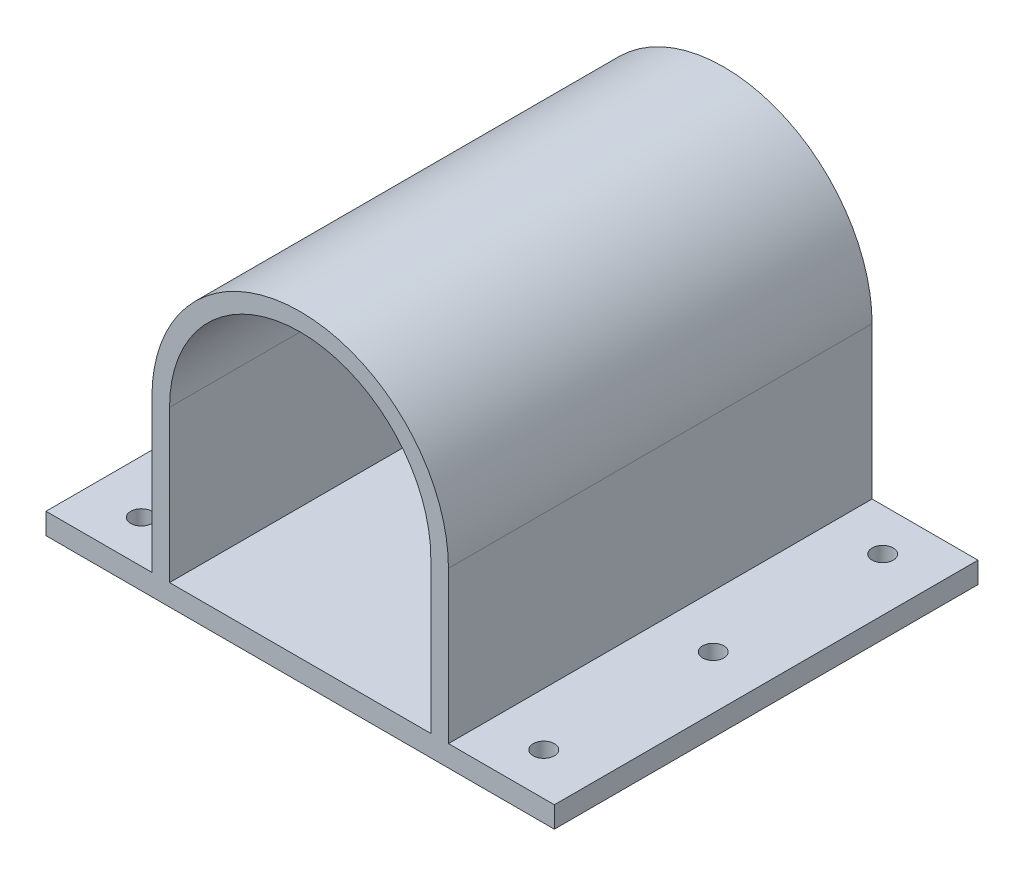
SolidWorks part; units mm, degrees
ref_plane "Front Plane" through (0, 0, 0) normal (0, 0, 1) x (1, 0, 0)
ref_plane "Top Plane" through (0, 0, 0) normal (0, 1, 0) x (1, 0, 0)
ref_plane "Right Plane" through (0, 0, 0) normal (1, 0, 0) x (0, 0, -1)
sketch "Sketch1" plane through (0, 0, 0) normal (0, 0, 1) x (1, 0, 0)
  line L0 (-21, 0) -> (-21, -21.5)
  line L1 (-21, -21.5) -> (-36, -21.5)
  line L2 (-36, -21.5) -> (-36, -24.5)
  line L3 (-36, -24.5) -> (36, -24.5)
  line L4 (36, -24.5) -> (36, -21.5)
  line L5 (36, -21.5) -> (21, -21.5)
  line L6 (21, -21.5) -> (21, 0)
  line L7 (0, 0) -> (-7, 0) construction
  line L8 (0, 0) -> (0, -15.5) construction
  line L9 (-21, -21.5) -> (21, -21.5) construction
  arc A0 (21, 0) -> (-21, 0) centre (0, 0) ccw
  circle A2 centre (0, -15.5) radius 1.65
  circle A3 centre (-13.4234, -7.75) radius 1.65
  circle A4 centre (-13.4234, 7.75) radius 1.65
  circle A5 centre (0, 15.5) radius 1.65
  circle A6 centre (13.4234, 7.75) radius 1.65
  circle A7 centre (13.4234, -7.75) radius 1.65
  circle A8 centre (0, 0) radius 18.5 construction
  circle A9 centre (-7, 0) radius 6.15
  point P15 (0, -18.5)
  point P27 (0, 0)
  dimension "D1" = 42
  dimension "D6" = 3
  dimension "D7" = 3.3
  dimension "D10" = 37
  dimension "D11" = 2.5
  dimension "D12" = 90
  dimension "D3" = 12.3
  dimension "D2" = 7
  dimension "D4" = 72
  dimension "D5" = 3
  dimension "D8" = 15.5
  dimension "D9" = 6
extrude "Boss-Extrude1" add sketch "Sketch1" along normal blind 60
sketch "Sketch2" plane through (0, 0, 60) normal (0, 0, 1) x (1, 0, 0)
  line L0 (-18.5, 0) -> (-18.5, -21.5)
  line L2 (-18.5, -21.5) -> (18.5, -21.5)
  line L3 (18.5, -21.5) -> (18.5, 0)
  line L4 (-21, -21.5) -> (-36, -21.5) construction
  arc A0 (18.5, 0) -> (-18.5, 0) centre (0, 0) ccw
  arc A1 (-18.5, 0) -> (18.5, 0) centre (0, 0) ccw construction
  dimension "D1" = 37
extrude "Cut-Extrude1" cut sketch "Sketch2" against normal blind 57
sketch "Sketch3" plane through (0, -21.5, 0) normal (0, 1, 0) x (1, 0, 0)
  line L0 (0, 0) -> (0, -60) construction
  line L1 (-21, -60) -> (21, -60) construction
  line L2 (-28.5, 0) -> (-28.5, -60) construction
  line L3 (-21, 0) -> (-36, 0) construction
  line L4 (-21, -60) -> (-36, -60) construction
  circle A0 centre (-28.5, -30) radius 1.5
  circle A1 centre (-28.5, -6) radius 1.5
  circle A2 centre (-28.5, -54) radius 1.5
  circle A3 centre (28.5, -54) radius 1.5
  circle A4 centre (28.5, -6) radius 1.5
  circle A5 centre (28.5, -30) radius 1.5
  dimension "D1" = 24
  dimension "D2" = 24
  dimension "D3" = 3
extrude "Cut-Extrude2" cut sketch "Sketch3" against normal through all
fillet "Fillet1" radius 6 1 edges at (-36, -23, 0)
